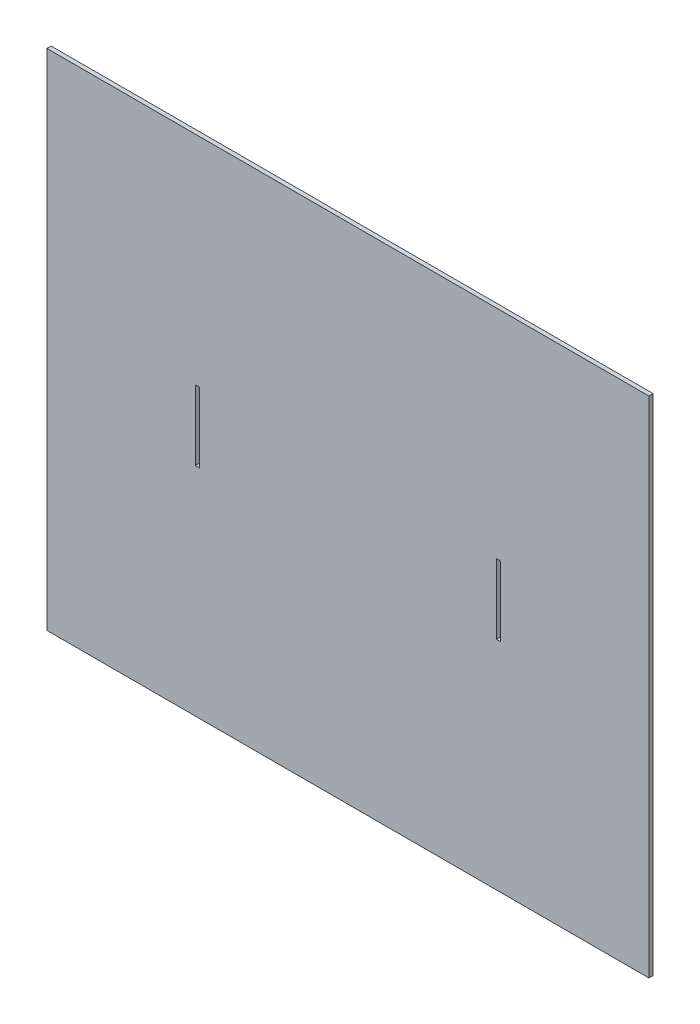
SolidWorks part; units mm, degrees
ref_plane "Plan de face" through (0, 0, 0) normal (0, 0, 1) x (1, 0, 0)
ref_plane "Plan de dessus" through (0, 0, 0) normal (0, 1, 0) x (1, 0, 0)
ref_plane "Plan de droite" through (0, 0, 0) normal (1, 0, 0) x (0, 0, -1)
sketch "Esquisse1" plane through (0, 0, 0) normal (0, 0, 1) x (1, 0, 0)
  line L1 (0, 0) -> (430, 0)
  line L2 (0, 0) -> (0, 360)
  line L3 (0, 360) -> (430, 360)
  line L4 (430, 0) -> (430, 360)
  line L8 (324, 205) -> (321, 205)
  line L9 (324, 205) -> (324, 155)
  line L10 (106, 205) -> (109, 205)
  line L11 (106, 205) -> (106, 155)
  line L12 (106, 155) -> (109, 155)
  line L13 (109, 205) -> (109, 155)
  line L14 (324, 155) -> (321, 155)
  line L15 (321, 205) -> (321, 155)
  dimension "D1" = 430
  dimension "D2" = 360
  dimension "D7" = 3
extrude "Boss.-Extru.1" add sketch "Esquisse1" along normal blind 3
